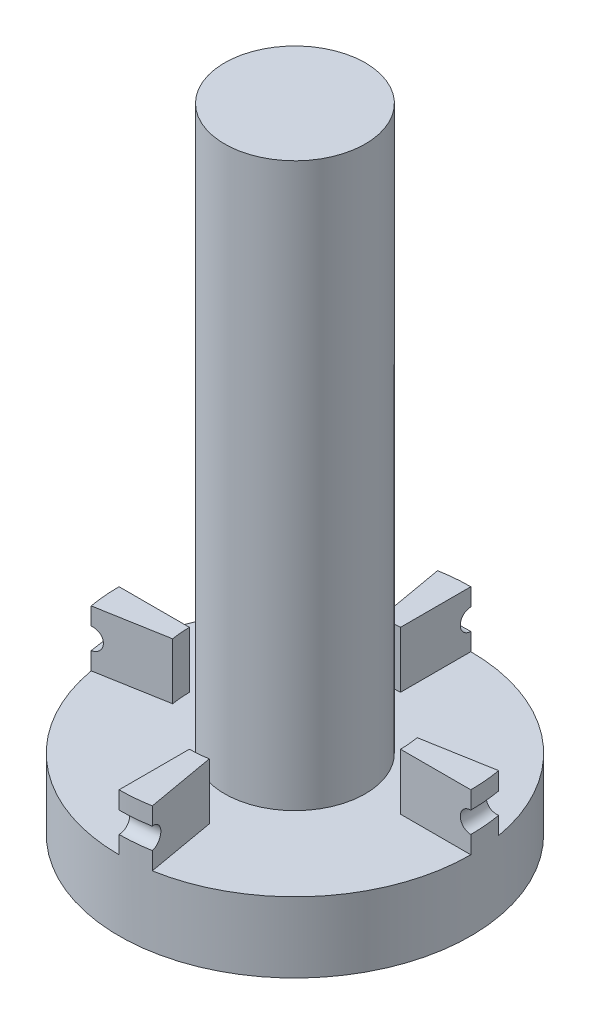
SolidWorks part; units mm, degrees
ref_plane "Front Plane" through (0, 0, 0) normal (0, 0, 1) x (1, 0, 0)
ref_plane "Top Plane" through (0, 0, 0) normal (0, 1, 0) x (1, 0, 0)
ref_plane "Right Plane" through (0, 0, 0) normal (1, 0, 0) x (0, 0, -1)
sketch "Sketch1" plane through (0, 0, 0) normal (0, 1, 0) x (1, 0, 0)
  circle A0 centre (0, 0) radius 5
  dimension "D1" = 10
extrude "Shaft" add sketch "Sketch1" along normal blind 45
ref_plane "Datum Plane" through (0, 0, 0) normal (0, -1, 0) x (-1, 0, 0)
sketch "Sketch3" plane through (0, 0, 0) normal (0, -1, 0) x (-1, 0, 0)
  circle A0 centre (0, 0) radius 12.5
  dimension "D1" = 25
extrude "Datum " add sketch "Sketch3" against normal blind 5
sketch "Sketch4" plane through (0, 0, 0) normal (1, 0, 0) x (0, 0, -1)
  line L0 (12.5, 5) -> (-12.5, 5) construction
  line L1 (12.5, 0) -> (12.5, 5) construction
  line L2 (12.5, 5) -> (-12.5, 5)
  line L3 (12.5, 0) -> (12.5, 5)
  line L4 (12.5, 7.75) -> (12.5, 9)
  line L5 (12.5, 5) -> (7.5, 5)
  line L6 (12.5, 5) -> (12.5, 6.25)
  line L7 (12.5, 9) -> (7.5, 9)
  line L8 (7.5, 5) -> (7.5, 9)
  arc A0 (12.5, 7.75) -> (12.5, 6.25) centre (12.5, 7) ccw
  dimension "D3" = 1.5
  dimension "D1" = 4
  dimension "D2" = 5
ref_axis "Wire Support Axis" through (0, 45, 0) along (0, -1, 0)
revolve "Wire Support" add sketch "Sketch4" angle 10 about axis through (0, 45, 0) along (0, -1, 0)
pattern_circular "Wire Support Pattern" count 4 every 90 about axis through (0, 45, 0) along (0, 1, 0) of "Wire Support"
sketch "Sketch6" plane through (0, 0, 0) normal (0, -1, 0) x (1, 0, 0)
  circle A0 centre (0, 0) radius 2.6
  dimension "D1" = 5.2
extrude "Hole" cut sketch "Sketch6" against normal blind 11
